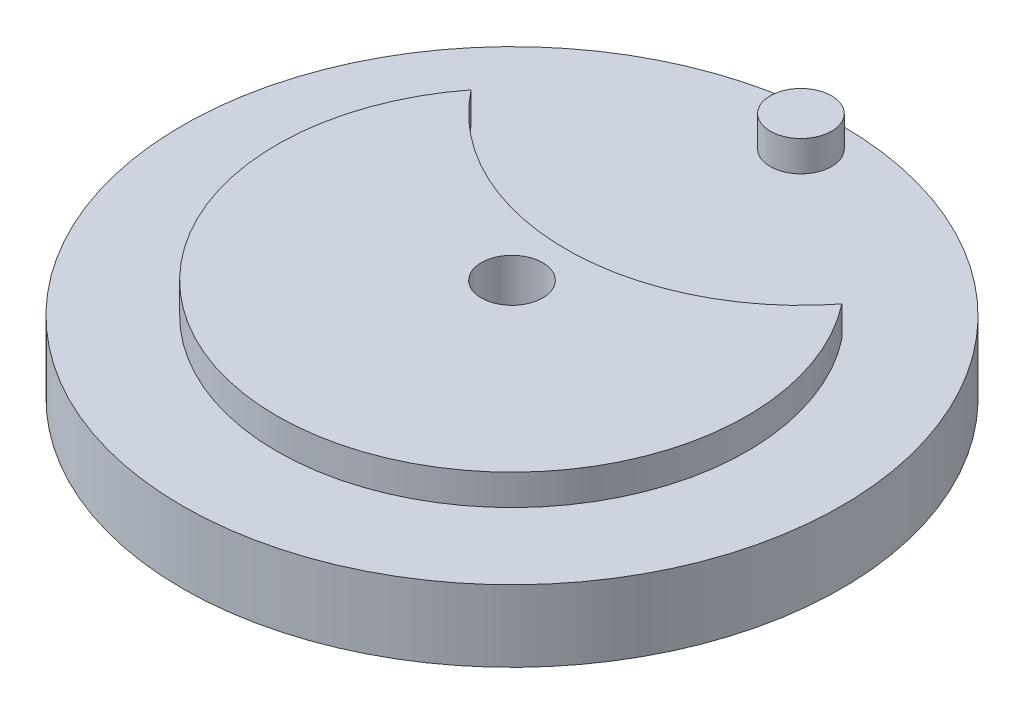
SolidWorks part; units mm, degrees
ref_plane "Front Plane" through (0, 0, 0) normal (0, 0, 1) x (1, 0, 0)
ref_plane "Top Plane" through (0, 0, 0) normal (0, 1, 0) x (1, 0, 0)
ref_plane "Right Plane" through (0, 0, 0) normal (1, 0, 0) x (0, 0, -1)
sketch "Sketch1" plane through (0, 0, 0) normal (0, 1, 0) x (1, 0, 0)
  circle A0 centre (0, 0) radius 64.5
  dimension "D1" = 129
extrude "Boss-Extrude1" add sketch "Sketch1" along normal blind 14
sketch "Sketch2" plane through (0, 14, 0) normal (0, 1, 0) x (1, 0, 0)
  circle A0 centre (0, 0) radius 46
  dimension "D1" = 92
extrude "Boss-Extrude2" add sketch "Sketch2" along normal blind 6
sketch "Sketch3" plane through (0, 20, 0) normal (0, 1, 0) x (1, 0, 0)
  circle A3 centre (0, 0) radius 56.55 construction
  circle A4 centre (0, 56.55) radius 46
  dimension "D1" = 113.1
  dimension "D2" = 92
extrude "Cut-Extrude3" cut sketch "Sketch3" against normal up to surface (6 mm away) up to face at (0, 14, 46)
sketch "Sketch4" plane through (0, 14, 0) normal (0, 1, 0) x (1, 0, 0)
  circle A0 centre (0, 0) radius 56.55 construction
  circle A1 centre (0, 56.55) radius 6
  dimension "D1" = 113.1
  dimension "D2" = 12
extrude "Boss-Extrude3" add sketch "Sketch4" along normal blind 6
sketch "Sketch6" plane through (0, 20, 0) normal (0, 1, 0) x (1, 0, 0)
  circle A0 centre (0, 0) radius 6
  dimension "D1" = 12
extrude "Cut-Extrude2" cut sketch "Sketch6" against normal through all
